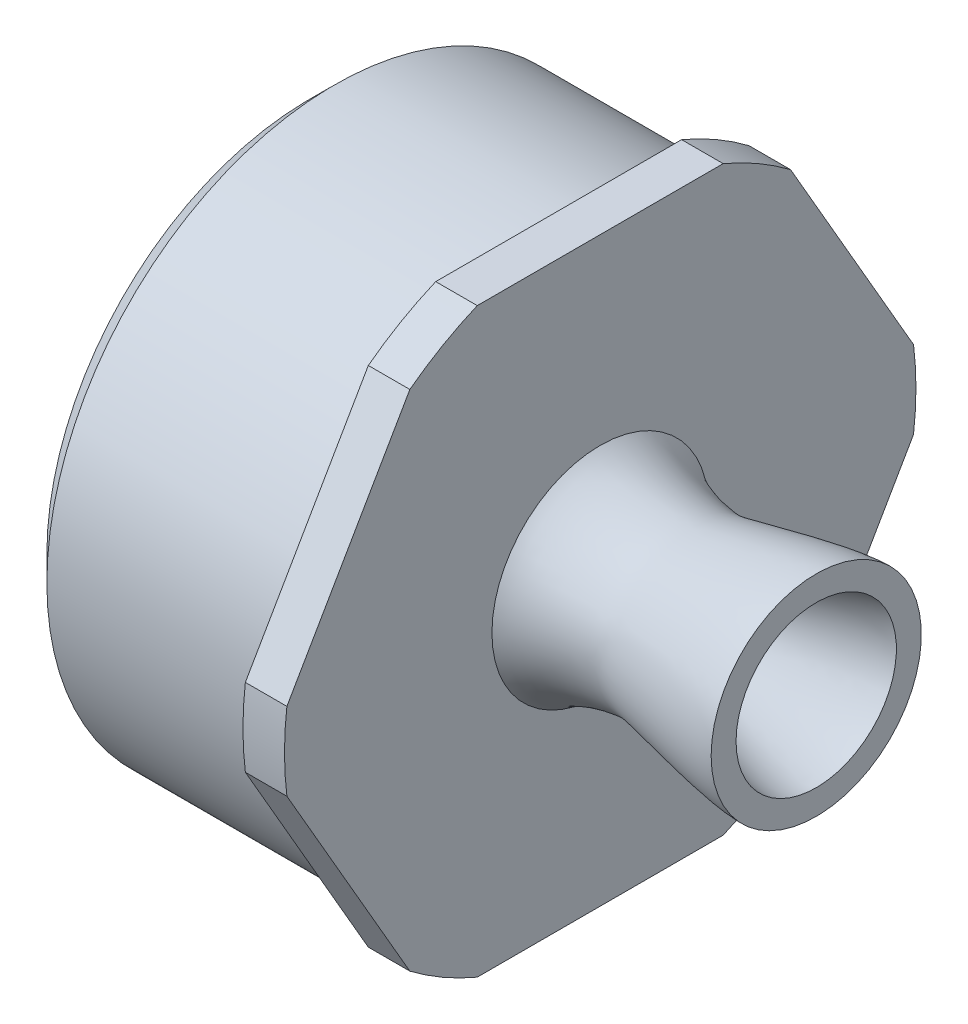
SolidWorks part; units mm, degrees
material "1.0401 (C15)"
ref_plane "Plano frontal" through (0, 0, 0) normal (0, 0, 1) x (1, 0, 0)
ref_plane "Plano superior" through (0, 0, 0) normal (0, 1, 0) x (1, 0, 0)
ref_plane "Plano direito" through (0, 0, 0) normal (1, 0, 0) x (0, 0, -1)
sketch "Esboço5" plane through (0, 0, 0) normal (0, 1, 0) x (1, 0, 0)
  line L4 (45, 0) -> (45, 16.038) construction
  line L10 (61, 0) -> (61, 12.65) construction
  line L11 (0, 0) -> (42.0295, 0) construction
  line L12 (0, 0) -> (0, 34.6) construction
  line L13 (0, 34.6) -> (30, 34.6) construction
  line L14 (30, 34.6) -> (30, 38)
  line L15 (30, 38) -> (35, 38)
  line L16 (35, 38) -> (35, 0) construction
  line L17 (0, 28.6) -> (0, 34.6) construction
  line L18 (35, 38) -> (35, 13.0345)
  line L19 (61, 12.65) -> (61, 9.65)
  line L20 (0, 31.6) -> (3, 34.6)
  line L21 (3, 34.6) -> (30, 34.6)
  line L22 (0, 31.6) -> (0, 28.6)
  spline S0 degree 3 poles (35, 13.0345) (38.1087, 10.6485) (43.8355, 9.8618) (46.5985, 10.0407) (57.2649, 12.6502) (61, 12.65) knots 0 0 0 0 0.394117 0.494117 1 1 1 1
  spline S1 degree 3 poles (0, 28.6) (20.3139, 8.9562) (43.7846, 4.8354) (46.6783, 5.0043) (57.2916, 9.662) (61, 9.65) knots 0 0 0 0 0.416422 0.516422 1 1 1 1
  point P15 (35, 7.0345)
  dimension "D1" = 4.95
  dimension "D2" = 5
  dimension "D3" = 10
  dimension "D4" = 5
  dimension "D5" = 3
  dimension "D6" = 16
  dimension "D7" = 9.65
  dimension "D8" = 6
  dimension "D9" = 34.6
  dimension "D10" = 38
  dimension "D11" = 45
  dimension "D12" = 6
  dimension "D13" = 45
  dimension "D14" = 3
revolve "Revolução2" add sketch "Esboço5" angle 360 about L11
sketch "Esboço30" plane through (35, 0, 0) normal (1, 0, 0) x (0, 0, -1)
  line L0 (-14.7986, 35) -> (14.7986, 35)
  line L1 (-35, -35) -> (35, -35) construction
  line L2 (-35, -35) -> (-35, 35) construction
  line L3 (-35, 35) -> (35, 35) construction
  line L4 (35, -35) -> (35, 35) construction
  line L5 (-35, -35) -> (35, 35) construction
  line L6 (-35, 35) -> (35, -35) construction
  arc A0 (-14.7986, 35) -> (14.7986, 35) centre (0, 0) cw
  circle A1 centre (0, 0) radius 38 construction
  point P0 (0, 0)
  dimension "D1" = 70
extrude "Corte-extrusão1" cut sketch "Esboço30" against normal up to next
pattern_circular "PadrãoCircular1" count 6 over 360 about axis through (0, 0, 0) along (1, 0, 0) of "Corte-extrusão1"
